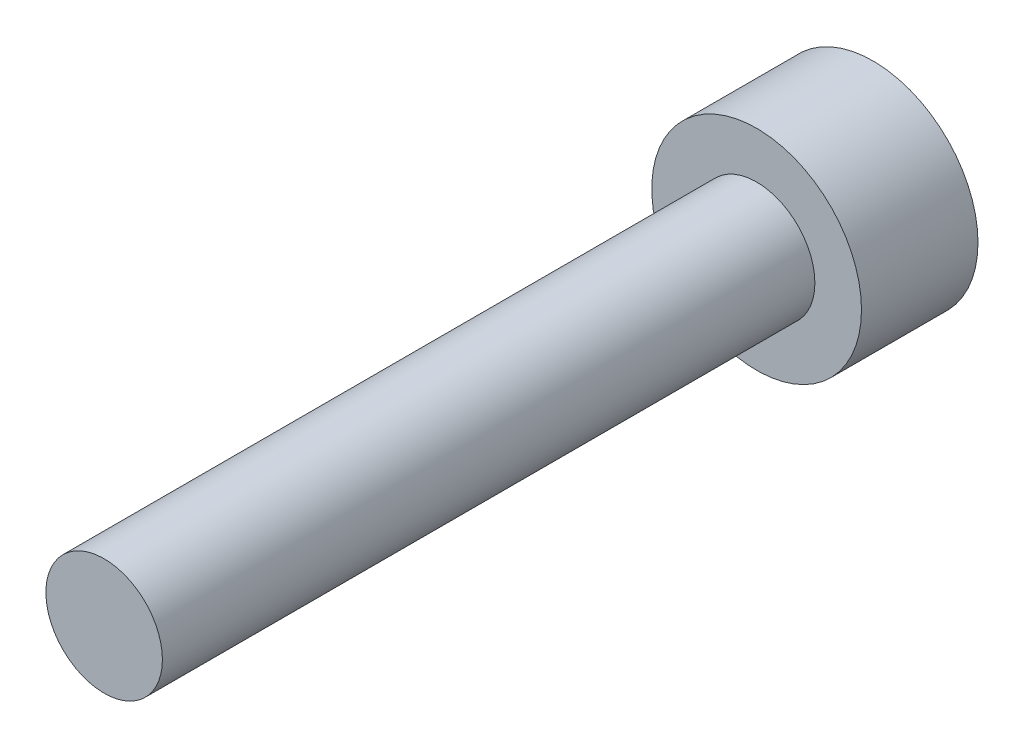
SolidWorks part; units mm, degrees
material "Acero aleado"
ref_plane "Alzado" through (0, 0, 0) normal (0, 0, 1) x (1, 0, 0)
ref_plane "Planta" through (0, 0, 0) normal (0, 1, 0) x (1, 0, 0)
ref_plane "Vista lateral" through (0, 0, 0) normal (1, 0, 0) x (0, 0, -1)
sketch "Croquis1" plane through (0, 0, 0) normal (0, 0, 1) x (1, 0, 0)
  circle A0 centre (0, 0) radius 2.25
  dimension "D1" = 4.5
extrude "Cabeza" add sketch "Croquis1" along normal blind 2.5 from offset 2.5
sketch "Croquis2" plane through (0, 0, 0) normal (0, 0, 1) x (1, 0, 0)
  circle A0 centre (0, 0) radius 1.25
  dimension "D1" = 2.5
extrude "Cuerpo" add sketch "Croquis2" along normal blind 14
sketch "Croquis3" plane through (0, 0, 0) normal (0, 0, 1) x (1, 0, 0)
  line L0 (1.1547, 0) -> (0.5774, 1)
  line L1 (0.5774, 1) -> (-0.5774, 1)
  line L2 (-0.5774, 1) -> (-1.1547, 0)
  line L3 (-1.1547, 0) -> (-0.5774, -1)
  line L4 (-0.5774, -1) -> (0.5774, -1)
  line L5 (0.5774, -1) -> (1.1547, 0)
  dimension "D1" = 1.1547
  dimension "D2" = 0.5774
  dimension "D3" = 1
  dimension "D4" = 0.5774
  dimension "D5" = 1
  dimension "D6" = 1.1547
  dimension "D7" = 0.5774
  dimension "D8" = 1
  dimension "D9" = 0.5774
  dimension "D10" = 1
extrude "Hexagono_interior" cut sketch "Croquis3" along normal blind 1.1 from offset 2.5
